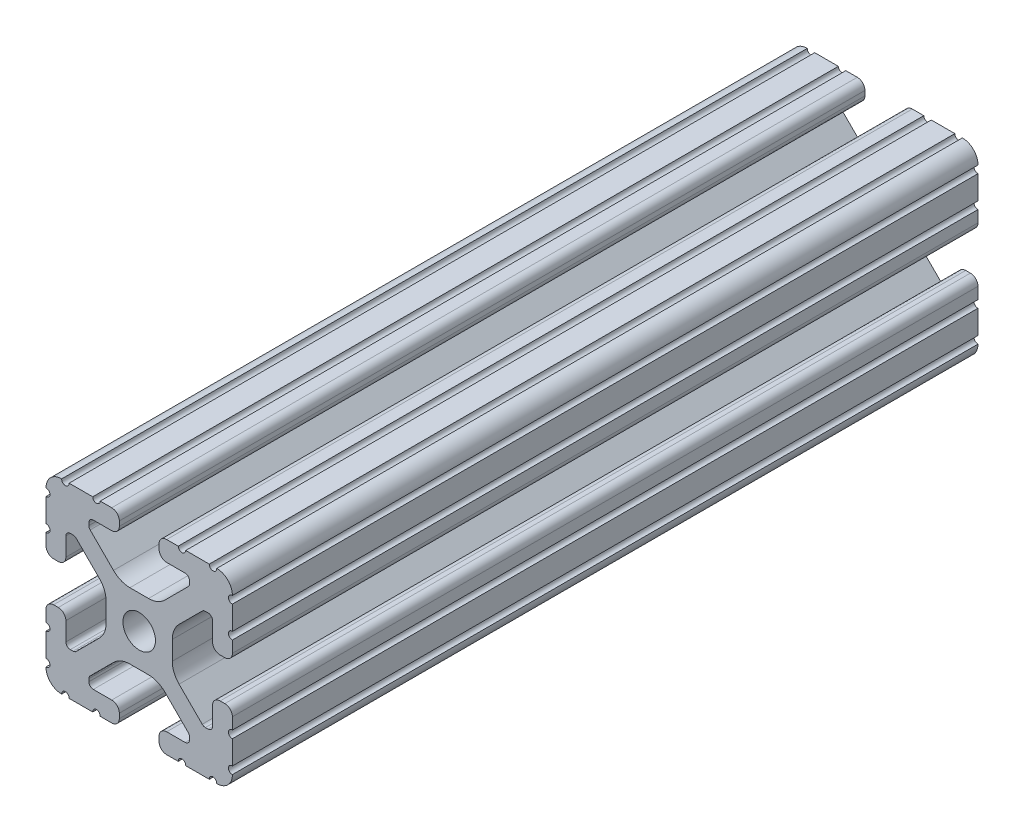
SolidWorks part; units mm, degrees
material "6061 Alloy"
ref_plane "Front Plane" through (0, 0, 0) normal (0, 0, 1) x (1, 0, 0)
ref_plane "Top Plane" through (0, 0, 0) normal (0, 1, 0) x (1, 0, 0)
ref_plane "Right Plane" through (0, 0, 0) normal (1, 0, 0) x (0, 0, -1)
sketch "Sketch1" plane through (0, 0, 0) normal (0, 0, 1) x (1, 0, 0)
  line L0 (0, 25.6181) -> (0, -24.623) construction
  line L1 (-20.8943, 0) -> (20.4607, 0) construction
  line L2 (-10.0229, 12.9148) -> (-5.2522, 8.144)
  line L3 (-10.287, 14.0843) -> (-10.287, 13.5524)
  line L4 (-5.6176, 14.986) -> (-9.3853, 14.986)
  line L5 (-4.064, 17.4964) -> (-4.064, 16.5396)
  line L6 (-7.9742, 19.05) -> (-5.6176, 19.05)
  line L7 (-14.3277, 19.05) -> (-9.4982, 19.05)
  line L8 (-19.05, 9.4961) -> (-19.05, 14.3277)
  line L9 (-19.05, 5.6176) -> (-19.05, 7.9763)
  line L10 (-16.5396, 4.064) -> (-17.4964, 4.064)
  line L11 (-14.986, 9.3853) -> (-14.986, 5.6176)
  line L12 (-13.516, 10.287) -> (-14.0843, 10.287)
  line L13 (-8.1476, 5.2921) -> (-12.8784, 10.0229)
  line L14 (-6.7564, -1.9335) -> (-6.7564, 1.9335)
  line L15 (-12.8784, -10.0229) -> (-8.1476, -5.2921)
  line L16 (-14.0843, -10.287) -> (-13.516, -10.287)
  line L17 (-14.986, -5.6176) -> (-14.986, -9.3853)
  line L18 (-17.4964, -4.064) -> (-16.5396, -4.064)
  line L19 (-19.05, -7.9763) -> (-19.05, -5.6176)
  line L20 (-19.05, -14.3277) -> (-19.05, -9.4961)
  line L21 (-9.4961, -19.05) -> (-14.3277, -19.05)
  line L22 (-5.6176, -19.05) -> (-7.9763, -19.05)
  line L23 (-4.064, -17.4964) -> (-4.064, -16.5396)
  line L24 (10.0229, -12.9148) -> (5.2522, -8.144)
  line L25 (10.287, -14.0843) -> (10.287, -13.5524)
  line L26 (5.6176, -14.986) -> (9.3853, -14.986)
  line L28 (-1.9022, 6.7564) -> (1.9022, 6.7564)
  line L29 (-1.9022, -6.7564) -> (1.9022, -6.7564)
  line L31 (-5.6176, -14.986) -> (-9.3853, -14.986)
  line L32 (-10.287, -14.0843) -> (-10.287, -13.5524)
  line L33 (-10.0229, -12.9148) -> (-5.2522, -8.144)
  line L66 (4.064, -16.5396) -> (4.064, -17.4964)
  line L67 (5.6176, -19.05) -> (7.9763, -19.05)
  line L68 (9.4961, -19.05) -> (14.3277, -19.05)
  line L69 (19.05, -14.3277) -> (19.05, -9.4961)
  line L70 (19.05, -7.9763) -> (19.05, -5.6176)
  line L71 (17.4964, -4.064) -> (16.5396, -4.064)
  line L72 (14.986, -5.6176) -> (14.986, -9.3853)
  line L73 (14.0843, -10.287) -> (13.516, -10.287)
  line L74 (12.8784, -10.0229) -> (8.1476, -5.2921)
  line L75 (6.7564, -1.9335) -> (6.7564, 1.9335)
  line L76 (8.1476, 5.2921) -> (12.8784, 10.0229)
  line L77 (13.516, 10.287) -> (14.0843, 10.287)
  line L78 (14.986, 9.3853) -> (14.986, 5.6176)
  line L79 (16.5396, 4.064) -> (17.4964, 4.064)
  line L80 (19.05, 5.6176) -> (19.05, 7.9763)
  line L81 (19.05, 9.4961) -> (19.05, 14.3277)
  line L82 (14.3277, 19.05) -> (9.4982, 19.05)
  line L83 (7.9742, 19.05) -> (5.6176, 19.05)
  line L84 (4.064, 17.4964) -> (4.064, 16.5396)
  line L85 (5.6176, 14.986) -> (9.3853, 14.986)
  line L86 (10.287, 14.0843) -> (10.287, 13.5524)
  line L87 (10.0229, 12.9148) -> (5.2522, 8.144)
  arc A0 (-10.0229, 12.9148) -> (-10.287, 13.5524) centre (-9.3853, 13.5524) cw
  circle A1 centre (0, 0) radius 3.3274
  arc A2 (-10.287, 14.0843) -> (-9.3853, 14.986) centre (-9.3853, 14.0843) cw
  arc A3 (-4.064, 16.5396) -> (-5.6176, 14.986) centre (-5.6176, 16.5396) cw
  arc A4 (-5.6176, 19.05) -> (-4.064, 17.4964) centre (-5.6176, 17.4964) cw
  arc A5 (-7.9742, 19.05) -> (-9.4982, 19.05) centre (-8.7362, 19.05) cw
  arc A6 (-14.3277, 19.05) -> (-15.8475, 19.05) centre (-15.0876, 18.9933) cw
  arc A7 (-19.05, 15.8475) -> (-15.8475, 19.05) centre (-15.8751, 15.8751) cw
  arc A8 (-19.05, 15.8475) -> (-19.05, 14.3277) centre (-18.9933, 15.0876) cw
  arc A9 (-19.05, 9.4961) -> (-19.05, 7.9763) centre (-18.9933, 8.7362) cw
  arc A10 (-17.4964, 4.064) -> (-19.05, 5.6176) centre (-17.4964, 5.6176) cw
  arc A11 (-14.986, 5.6176) -> (-16.5396, 4.064) centre (-16.5396, 5.6176) cw
  arc A12 (-14.986, 9.3853) -> (-14.0843, 10.287) centre (-14.0843, 9.3853) cw
  arc A13 (-13.516, 10.287) -> (-12.8784, 10.0229) centre (-13.516, 9.3853) cw
  arc A14 (-8.1476, 5.2921) -> (-6.7564, 1.9335) centre (-11.5062, 1.9335) cw
  arc A15 (-6.7564, -1.9335) -> (-8.1476, -5.2921) centre (-11.5062, -1.9335) cw
  arc A16 (-12.8784, -10.0229) -> (-13.516, -10.287) centre (-13.516, -9.3853) cw
  arc A17 (-14.0843, -10.287) -> (-14.986, -9.3853) centre (-14.0843, -9.3853) cw
  arc A18 (-16.5396, -4.064) -> (-14.986, -5.6176) centre (-16.5396, -5.6176) cw
  arc A19 (-19.05, -5.6176) -> (-17.4964, -4.064) centre (-17.4964, -5.6176) cw
  arc A20 (-19.05, -7.9763) -> (-19.05, -9.4961) centre (-18.9933, -8.7362) cw
  arc A21 (-19.05, -14.3277) -> (-19.05, -15.8475) centre (-18.9933, -15.0876) cw
  arc A22 (-15.8475, -19.05) -> (-19.05, -15.8475) centre (-15.8751, -15.8751) cw
  arc A23 (-15.8475, -19.05) -> (-14.3277, -19.05) centre (-15.0876, -18.9933) cw
  arc A24 (-9.4961, -19.05) -> (-7.9763, -19.05) centre (-8.7362, -18.9933) cw
  arc A25 (-4.064, -17.4964) -> (-5.6176, -19.05) centre (-5.6176, -17.4964) cw
  arc A26 (-5.2522, -8.144) -> (-1.9022, -6.7564) centre (-1.9022, -11.494) cw
  arc A27 (1.9022, -6.7564) -> (5.2522, -8.144) centre (1.9022, -11.494) cw
  arc A28 (10.0229, -12.9148) -> (10.287, -13.5524) centre (9.3853, -13.5524) cw
  arc A29 (10.287, -14.0843) -> (9.3853, -14.986) centre (9.3853, -14.0843) cw
  arc A30 (4.064, -16.5396) -> (5.6176, -14.986) centre (5.6176, -16.5396) cw
  arc A31 (-4.064, -16.5396) -> (-5.6176, -14.986) centre (-5.6176, -16.5396) ccw
  arc A32 (-10.287, -14.0843) -> (-9.3853, -14.986) centre (-9.3853, -14.0843) ccw
  arc A33 (-10.0229, -12.9148) -> (-10.287, -13.5524) centre (-9.3853, -13.5524) ccw
  arc A79 (4.064, -17.4964) -> (5.6176, -19.05) centre (5.6176, -17.4964) ccw
  arc A80 (9.4961, -19.05) -> (7.9763, -19.05) centre (8.7362, -18.9933) ccw
  arc A81 (15.8475, -19.05) -> (14.3277, -19.05) centre (15.0876, -18.9933) ccw
  arc A82 (15.8475, -19.05) -> (19.05, -15.8475) centre (15.8751, -15.8751) ccw
  arc A83 (19.05, -14.3277) -> (19.05, -15.8475) centre (18.9933, -15.0876) ccw
  arc A84 (19.05, -7.9763) -> (19.05, -9.4961) centre (18.9933, -8.7362) ccw
  arc A85 (19.05, -5.6176) -> (17.4964, -4.064) centre (17.4964, -5.6176) ccw
  arc A86 (16.5396, -4.064) -> (14.986, -5.6176) centre (16.5396, -5.6176) ccw
  arc A87 (14.0843, -10.287) -> (14.986, -9.3853) centre (14.0843, -9.3853) ccw
  arc A88 (12.8784, -10.0229) -> (13.516, -10.287) centre (13.516, -9.3853) ccw
  arc A89 (6.7564, -1.9335) -> (8.1476, -5.2921) centre (11.5062, -1.9335) ccw
  arc A90 (8.1476, 5.2921) -> (6.7564, 1.9335) centre (11.5062, 1.9335) ccw
  arc A91 (13.516, 10.287) -> (12.8784, 10.0229) centre (13.516, 9.3853) ccw
  arc A92 (14.986, 9.3853) -> (14.0843, 10.287) centre (14.0843, 9.3853) ccw
  arc A93 (14.986, 5.6176) -> (16.5396, 4.064) centre (16.5396, 5.6176) ccw
  arc A94 (17.4964, 4.064) -> (19.05, 5.6176) centre (17.4964, 5.6176) ccw
  arc A95 (19.05, 9.4961) -> (19.05, 7.9763) centre (18.9933, 8.7362) ccw
  arc A96 (19.05, 15.8475) -> (19.05, 14.3277) centre (18.9933, 15.0876) ccw
  arc A97 (19.05, 15.8475) -> (15.8475, 19.05) centre (15.8751, 15.8751) ccw
  arc A98 (14.3277, 19.05) -> (15.8475, 19.05) centre (15.0876, 18.9933) ccw
  arc A99 (7.9742, 19.05) -> (9.4982, 19.05) centre (8.7362, 19.05) ccw
  arc A100 (5.6176, 19.05) -> (4.064, 17.4964) centre (5.6176, 17.4964) ccw
  arc A101 (4.064, 16.5396) -> (5.6176, 14.986) centre (5.6176, 16.5396) ccw
  arc A102 (10.287, 14.0843) -> (9.3853, 14.986) centre (9.3853, 14.0843) ccw
  arc A103 (10.0229, 12.9148) -> (10.287, 13.5524) centre (9.3853, 13.5524) ccw
  arc A104 (1.9022, 6.7564) -> (5.2522, 8.144) centre (1.9022, 11.494) ccw
  arc A105 (-5.2522, 8.144) -> (-1.9022, 6.7564) centre (-1.9022, 11.494) ccw
  dimension "D1" = 6.6548
  dimension "D2" = 19.05
  dimension "D3" = 38.1
  dimension "D4" = 20.574
  dimension "D5" = 13.5128
  dimension "D6" = 4.064
  dimension "D7" = 8.128
  dimension "D8" = 4.064
  dimension "D9" = 12.2936
extrude "Extrude1" add sketch "Sketch1" against normal blind 152.4
